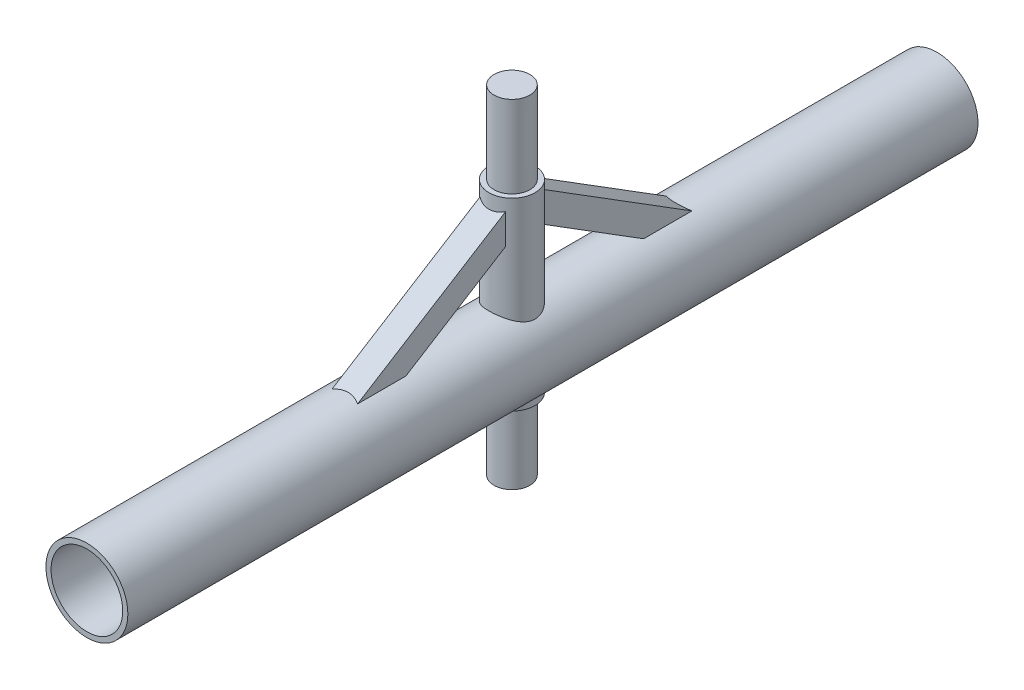
SolidWorks part; units mm, degrees
ref_plane "Front Plane" through (0, 0, 0) normal (0, 0, 1) x (1, 0, 0)
ref_plane "Top Plane" through (0, 0, 0) normal (0, 1, 0) x (1, 0, 0)
ref_plane "Right Plane" through (0, 0, 0) normal (1, 0, 0) x (0, 0, -1)
sketch "Sketch1" plane through (0, 0, 0) normal (0, 0, 1) x (1, 0, 0)
  circle A0 centre (0, 0) radius 40
  point P4 (0, 0)
  dimension "D1" = 80
extrude "Extrude-Thin1" add sketch "Sketch1" along normal mid plane 830 thin contours A0 thin type one direction reverse wall 5
sketch "Sketch2" plane through (0, 0, 0) normal (0, 1, 0) x (1, 0, 0)
  circle A0 centre (0, 0) radius 22.5
  dimension "D1" = 45
extrude "Extrude-Thin2" add sketch "Sketch2" along normal blind 140 and the other way blind 40 thin thin type one direction reverse wall 5
sketch "Sketch3" plane through (0, 140, 0) normal (0, 1, 0) x (1, 0, 0)
  circle A0 centre (0, 0) radius 17.5
  dimension "D1" = 35
extrude "Boss-Extrude1" add sketch "Sketch3" along normal blind 80 and the other way offset from surface (250 mm away) 70 other way up to face at (0, -40, 0)
sketch "Sketch4" plane through (0, 0, 0) normal (1, 0, 0) x (0, 0, -1)
  line L0 (0, 140) -> (-200, 15)
  line L1 (-22.5, 40) -> (-415, 40) construction
  line L4 (22.5, 140) -> (-22.5, 140) construction
  dimension "D1" = 200
  dimension "D2" = 140
  dimension "D3" = 25
extrude "Extrude-Thin3" add sketch "Sketch4" along normal mid plane 25 separate body thin thin type one direction reverse wall 25
mirror "Mirror1" about plane through (0, 0, 0) normal (0, 0, 1) of bodies 104
sketch "Sketch5" plane through (0, 0, -415) normal (0, 0, -1) x (-1, 0, 0)
  circle A1 centre (0, 0) radius 35
  dimension "D1" = 70
extrude "Cut-Extrude1" cut sketch "Sketch5" against normal blind 846
